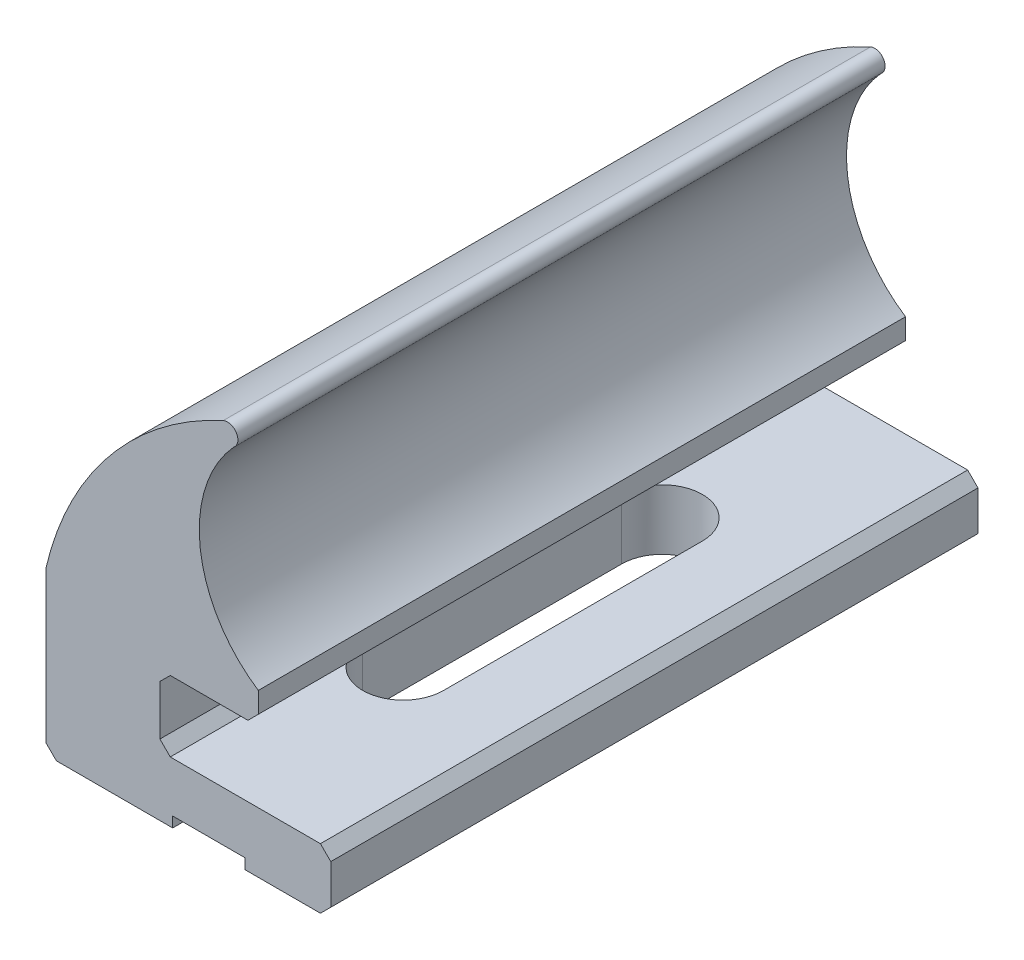
SolidWorks part; units mm, degrees
material "AISI Type A2 Tool Steel"
ref_plane "Front Plane" through (0, 0, 0) normal (0, 0, 1) x (1, 0, 0)
ref_plane "Top Plane" through (0, 0, 0) normal (0, 1, 0) x (1, 0, 0)
ref_plane "Right Plane" through (0, 0, 0) normal (1, 0, 0) x (0, 0, -1)
sketch "Sketch1" plane through (0, 0, 0) normal (0, 0, 1) x (1, 0, 0)
  line L0 (13.97, 15.6566) -> (13.97, 26.0248) construction
  line L10 (0, 12.7) -> (13.97, 12.7)
  line L21 (0, 12.7) -> (0, 20.6433)
  line L27 (13.97, 12.7) -> (13.97, 15.6566)
  line L29 (13.97, 15.6566) -> (5.588, 15.6566)
  line L31 (5.588, 15.6566) -> (5.588, 19.1193)
  line L33 (5.588, 19.1193) -> (10.414, 19.1193)
  line L34 (10.414, 19.1193) -> (10.414, 20.6433)
  arc A0 (10.414, 20.6433) -> (9.2063, 30.3737) centre (13.97, 26.0248) cw construction
  arc A1 (0, 20.6433) -> (8.6945, 31.247) centre (15.1249, 17.108) cw
  arc A2 (8.6945, 31.247) -> (9.2063, 30.3737) centre (8.9051, 30.7838) cw
  arc A3 (9.2063, 30.3737) -> (10.414, 20.6433) centre (13.97, 26.0248) ccw
  point P16 (8.001, 19.1193)
  dimension "D2" = 15.5326
  dimension "D6" = 2.9566
  dimension "D12" = 9.2063
  dimension "D13" = 8.9913
  dimension "D14" = 7.5197
  dimension "D15" = 13.3248
  dimension "D18" = 0.5088
  dimension "D4" = 13.97
  dimension "D16" = 13.97
  dimension "D22" = 6.4503
  dimension "D3" = 13.97
  dimension "D5" = 15.1249
  dimension "D7" = 3.4627
  dimension "D8" = 1.524
  dimension "D9" = 5.588
  dimension "D10" = 6.4193
  dimension "D11" = 3.556
  dimension "D17" = 4.826
  dimension "D19" = 12.7
  dimension "D20" = 10.414
  dimension "D21" = 3.556
  dimension "D25" = 8.9051
extrude "Boss-Extrude1" add sketch "Sketch1" against normal up to surface (31.75 mm away)
chamfer "Chamfer1" distance 0.508 angle 45 6 edges at (10.414, 19.1193, -15.875) (5.588, 15.6566, -15.875) (5.588, 19.1193, -15.875) (13.97, 12.7, -15.875) (13.97, 15.6566, -15.875) (0, 12.7, -15.875)
sketch "Sketch4" plane through (0, 12.7, 0) normal (0, -1, 0) x (1, 0, 0)
  line L0 (7.9932, 0) -> (7.9932, -31.75) construction
  line L1 (0.508, -31.75) -> (13.462, -31.75) construction
  line L2 (7.9932, -22.225) -> (7.9932, -9.525) construction
  line L3 (6.012, -22.225) -> (6.012, -9.525)
  line L4 (9.9744, -22.225) -> (9.9744, -9.525)
  line L5 (0.508, 0) -> (13.462, 0) construction
  line L6 (0, -31.75) -> (0, 0) construction
  arc A0 (6.012, -22.225) -> (9.9744, -22.225) centre (7.9932, -22.225) ccw
  arc A1 (9.9744, -9.525) -> (6.012, -9.525) centre (7.9932, -9.525) ccw
  point P6 (7.9932, -15.875)
  dimension "D3" = 1.9812
  dimension "D1" = 12.7
  dimension "D2" = 9.525
  dimension "D4" = 7.9932
extrude "Boss-Extrude2" add sketch "Sketch4" against normal up to surface (2.9566 mm away) up to face at (9.779, 15.6566, -15.875)
sketch "Sketch5" plane through (0, 12.7, 0) normal (0, -1, 0) x (1, 0, 0)
  line L2 (6.012, -22.225) -> (6.012, -9.525) construction
  line L3 (6.012, -22.225) -> (6.012, -9.525)
  line L4 (7.9932, 0) -> (7.9932, -31.75) construction
  line L5 (9.9744, -22.225) -> (9.9744, -9.525) construction
  line L6 (7.9932, 0) -> (7.9932, -31.75) construction
  line L7 (9.9744, -22.225) -> (9.9744, -9.525)
  arc A0 (6.012, -22.225) -> (9.9744, -22.225) centre (7.9932, -22.225) ccw construction
  arc A1 (9.9744, -9.525) -> (6.012, -9.525) centre (7.9932, -9.525) ccw construction
  arc A2 (6.012, -22.225) -> (9.9744, -22.225) centre (7.9932, -22.225) ccw
  arc A3 (9.9744, -9.525) -> (6.012, -9.525) centre (7.9932, -9.525) ccw
extrude "Cut-Extrude1" cut sketch "Sketch5" against normal up to next
sketch "Sketch7" plane through (0, 0, 0) normal (0, 0, 1) x (1, 0, 0)
  line L0 (6.012, 12.7) -> (9.9744, 12.7) construction
  line L2 (6.2152, 12.192) -> (9.7712, 12.192)
  line L3 (6.2152, 12.192) -> (6.2152, 13.208)
  line L4 (6.2152, 13.208) -> (9.7712, 13.208)
  line L5 (9.7712, 12.192) -> (9.7712, 13.208)
  line L6 (6.2152, 12.192) -> (9.7712, 13.208) construction
  line L7 (6.2152, 13.208) -> (9.7712, 12.192) construction
  point P4 (7.9932, 12.7)
  dimension "D1" = 1.016
  dimension "D2" = 3.556
extrude "Cut-Extrude2" cut sketch "Sketch7" against normal up to next
